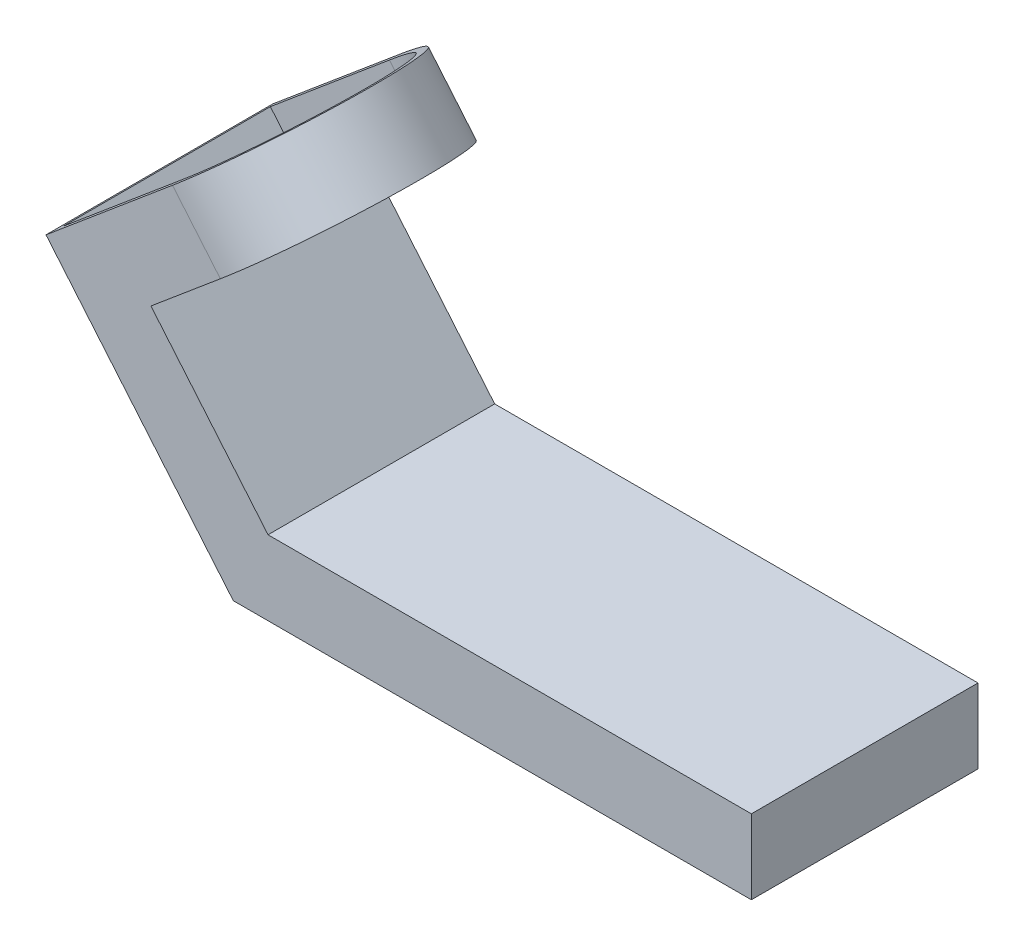
SolidWorks part; units mm, degrees
material "Laiton"
ref_plane "Plan de face" through (0, 0, 0) normal (0, 0, 1) x (1, 0, 0)
ref_plane "Plan de dessus" through (0, 0, 0) normal (0, 1, 0) x (1, 0, 0)
ref_plane "Plan de droite" through (0, 0, 0) normal (1, 0, 0) x (0, 0, -1)
sketch "Esquisse1" plane through (0, 0, 0) normal (0, 0, 1) x (1, 0, 0)
  line L0 (0, 0) -> (160, 0) construction
  line L1 (0, 0) -> (-57.8509, 68.944)
  line L2 (-57.8509, 68.944) -> (-18.7826, 101.7262)
  line L3 (-18.7826, 101.7262) -> (-3.9985, 84.1071)
  line L4 (-3.9985, 84.1071) -> (-25.4477, 66.1091)
  line L5 (-25.4477, 66.1091) -> (10.7251, 23)
  line L6 (10.7251, 23) -> (160, 23)
  line L7 (160, 23) -> (160, 0)
  line L8 (160, 0) -> (0, 0)
  dimension "D1" = 160
  dimension "D2" = 50
  dimension "D3" = 23
  dimension "D4" = 23
  dimension "D5" = 23
  dimension "D6" = 90
  dimension "D7" = 51
extrude "Boss.-Extru.1" add sketch "Esquisse1" against normal blind 70
sketch "Esquisse2" plane through (-57.8509, 68.944, 0) normal (-0.6428, 0.766, 0) x (0.766, 0.6428, 0)
  line L0 (137.3512, 0) -> (23, 0) construction
  line L1 (51, 70) -> (51, 0)
  arc A0 (51, 70) -> (51, 0) centre (51, 35) cw
  dimension "D1" = 35
extrude "Boss.-Extru.2" add sketch "Esquisse2" against normal blind 23
sketch "Esquisse3" plane through (-57.8509, 68.944, 0) normal (-0.6428, 0.766, 0) x (0.766, 0.6428, 0)
  circle A0 centre (51, 35) radius 9.5
  dimension "D1" = 19
extrude "Enlèv. mat.-Extru.1" cut sketch "Esquisse3" against normal up to next
shell "Coque1" thickness 3
equation "\"A\" = 50deg"
equation "\"B\" = 70"
equation "\"C\" = 160"
equation "\"D\"= 23"
equation "\"D1@Esquisse1\"=\"C\""
equation "\"D2@Esquisse1\"=\"A\""
equation "\"D3@Esquisse1\"=\"D\""
equation "\"D4@Esquisse1\"=\"D\""
equation "\"D5@Esquisse1\"=\"D\""
equation "\"D1@Boss.-Extru.1\"=\"B\""
equation "\"D1@Esquisse2\"=\"B\" / 2"
equation "\"D1@Boss.-Extru.2\"=\"D\""
